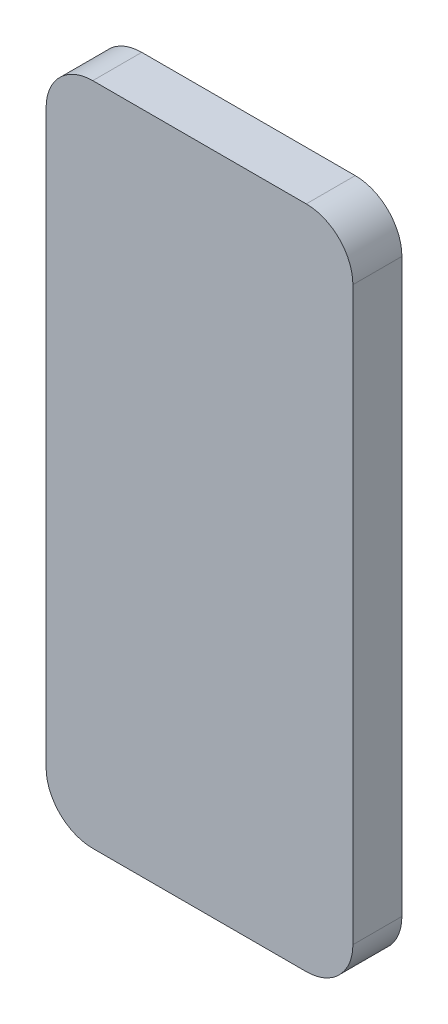
SolidWorks part; units mm, degrees
ref_plane "정면" through (0, 0, 0) normal (0, 0, 1) x (1, 0, 0)
ref_plane "윗면" through (0, 0, 0) normal (0, 1, 0) x (1, 0, 0)
ref_plane "우측면" through (0, 0, 0) normal (1, 0, 0) x (0, 0, -1)
sketch "스케치1" plane through (0, 0, 0) normal (0, 0, 1) x (1, 0, 0)
  line L1 (-19.725, 42.75) -> (19.725, 42.75)
  line L2 (-19.725, 42.75) -> (-19.725, -42.75)
  line L3 (-19.725, -42.75) -> (19.725, -42.75)
  line L4 (19.725, 42.75) -> (19.725, -42.75)
  line L5 (-19.725, 42.75) -> (19.725, -42.75) construction
  line L6 (-19.725, -42.75) -> (19.725, 42.75) construction
  point P0 (0, 0)
  dimension "D1" = 85.5
  dimension "D2" = 39.45
extrude "보스-돌출1" add sketch "스케치1" along normal blind 6.3
fillet "필렛1" radius 6 4 edges at (19.725, -42.75, 3.15) (-19.725, -42.75, 3.15) (-19.725, 42.75, 3.15) (19.725, 42.75, 3.15)
sketch "스케치2" plane through (0, 0, 0) normal (0, 0, -1) x (-1, 0, 0)
  line L0 (-19.725, -36.75) -> (-19.725, 36.75) construction
  line L1 (-13.725, 42.75) -> (13.725, 42.75) construction
  line L2 (0, 0) -> (0, 42.75) construction
  line L3 (0, 42.75) -> (0, 0) construction
  line L4 (0, 0) -> (19.725, 0) construction
  line L5 (19.725, 36.75) -> (19.725, -36.75) construction
  circle A0 centre (-11.225, 32.25) radius 4.25
  circle A1 centre (11.225, 32.25) radius 4.25
  circle A2 centre (0, 32.25) radius 4.25
  circle A3 centre (-11.225, 22.25) radius 4.25
  circle A4 centre (0, 22.25) radius 4.25
  circle A5 centre (11.225, 22.25) radius 4.25
  circle A6 centre (-11.225, 12.25) radius 4.25
  circle A7 centre (0, 12.25) radius 4.25
  circle A8 centre (11.225, 12.25) radius 4.25
  circle A9 centre (-11.225, 2.25) radius 4.25
  circle A10 centre (0, 2.25) radius 4.25
  circle A11 centre (11.225, 2.25) radius 4.25
  circle A12 centre (-11.225, -7.75) radius 4.25
  circle A13 centre (0, -7.75) radius 4.25
  circle A14 centre (11.225, -7.75) radius 4.25
  circle A15 centre (-11.225, -17.75) radius 4.25
  circle A16 centre (0, -17.75) radius 4.25
  circle A17 centre (11.225, -17.75) radius 4.25
  circle A18 centre (-11.225, -27.75) radius 4.25
  circle A19 centre (0, -27.75) radius 4.25
  circle A20 centre (11.225, -27.75) radius 4.25
  dimension "D2" = 8.5
  dimension "D4" = 8.5
  dimension "D1" = 8.5
  dimension "D3" = 10.5
  dimension "D5" = 7
extrude "보스-돌출2" add sketch "스케치2" along normal blind 0.5
